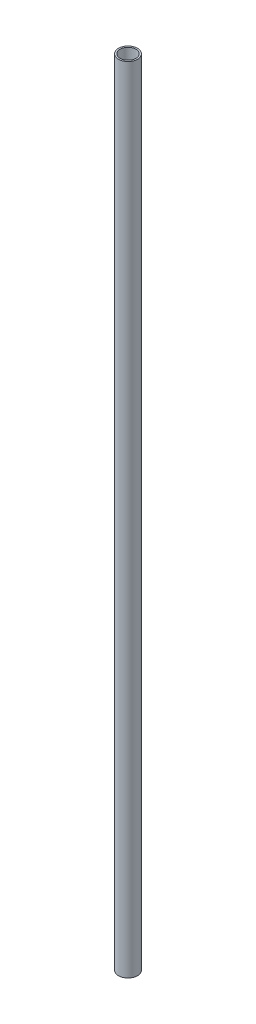
SolidWorks part; units mm, degrees
material "6061-O (SS)"
ref_plane "Front Plane" through (0, 0, 0) normal (0, 0, 1) x (1, 0, 0)
ref_plane "Top Plane" through (0, 0, 0) normal (0, 1, 0) x (1, 0, 0)
ref_plane "Right Plane" through (0, 0, 0) normal (1, 0, 0) x (0, 0, -1)
sketch "Sketch1" plane through (0, 0, 0) normal (0, 1, 0) x (1, 0, 0)
  circle A0 centre (0, 0) radius 6
  circle A1 centre (0, 0) radius 5
  dimension "D1" = 12
  dimension "D2" = 1
extrude "Boss-Extrude1" add sketch "Sketch1" along normal blind 500
